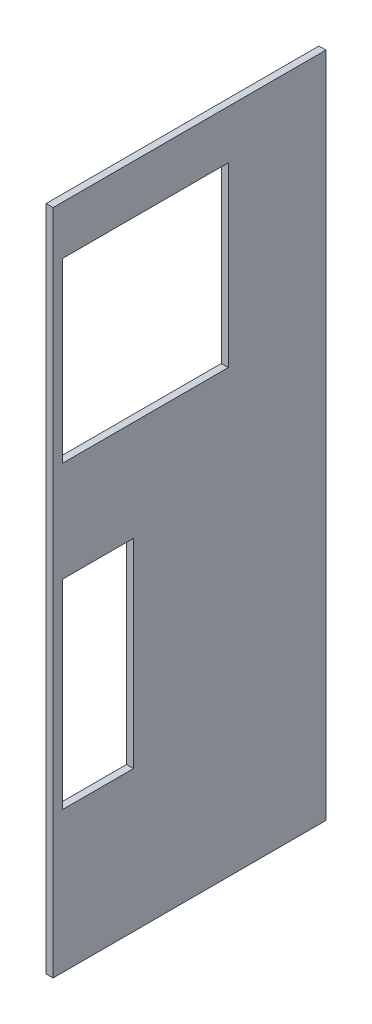
SolidWorks part; units mm, degrees
ref_plane "Спереди" through (0, 0, 0) normal (0, 0, 1) x (1, 0, 0)
ref_plane "Сверху" through (0, 0, 0) normal (0, 1, 0) x (1, 0, 0)
ref_plane "Справа" through (0, 0, 0) normal (1, 0, 0) x (0, 0, -1)
ref_plane "Плоскость4" through (0.5, 0, 0) normal (-1, 0, 0) x (0, -1, 0)
sketch "Эскиз1" plane through (0.5, 0, 0) normal (-1, 0, 0) x (0, -1, 0)
  line L0 (-5.85, 42.25) -> (-100.85, 42.25)
  line L1 (-100.85, 42.25) -> (-100.85, 3.4)
  line L2 (-100.85, 3.4) -> (-5.85, 3.4)
  line L3 (-5.85, 3.4) -> (-5.85, 42.25)
extrude "Бобышка-Вытянуть1" add sketch "Эскиз1" against normal blind 1
sketch "Эскиз2" plane through (0.5, 0, 0) normal (-1, 0, 0) x (0, 0, 1)
  line L0 (40.4, 53.85) -> (32.3, 53.85) construction
  line L1 (40.9, 25.95) -> (30.8, 25.95)
  line L2 (40.9, 25.95) -> (40.9, 54.35)
  line L3 (40.9, 54.35) -> (30.8, 54.35)
  line L4 (30.8, 25.95) -> (30.8, 54.35)
  line L5 (32.3, 26.45) -> (40.4, 26.45) construction
  line L6 (32.3, 30.965) -> (32.3, 34.095) construction
  line L7 (17.8, 93.4) -> (17.8, 89.095) construction
  line L8 (17.3, 68.65) -> (40.9, 68.65)
  line L9 (17.3, 68.65) -> (17.3, 93.9)
  line L10 (17.3, 93.9) -> (40.9, 93.9)
  line L11 (40.9, 68.65) -> (40.9, 93.9)
  line L12 (17.8, 93.4) -> (40.4, 93.4) construction
  line L13 (17.8, 69.15) -> (40.4, 69.15) construction
  line L14 (40.4, -6.55) -> (40.4, 122.15) construction
  dimension "D1" = 0.5
  dimension "D2" = 0.5
  dimension "D3" = 1.5
  dimension "D4" = 0.5
  dimension "D5" = 0.5
  dimension "D6" = 0.5
  dimension "D7" = 0.5
  dimension "D8" = 0.5
extrude "Вырез-Вытянуть1" cut sketch "Эскиз2" against normal blind 10
